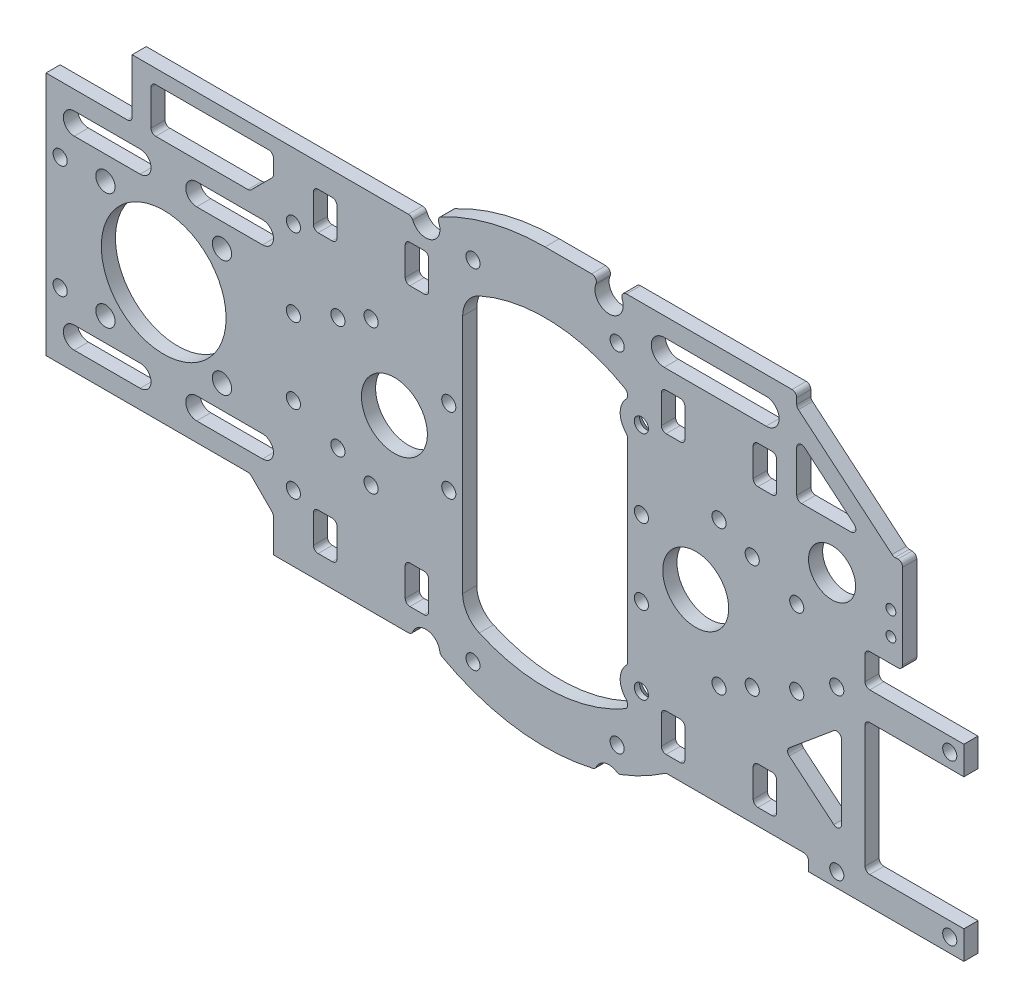
SolidWorks part; units mm, degrees
material "Thornel Mat VMA"
ref_plane "前视基准面" through (0, 0, 0) normal (0, 0, 1) x (1, 0, 0)
ref_plane "上视基准面" through (0, 0, 0) normal (0, 1, 0) x (1, 0, 0)
ref_plane "右视基准面" through (0, 0, 0) normal (1, 0, 0) x (0, 0, -1)
sketch "草图1" plane through (0, 0, 0) normal (0, 0, 1) x (1, 0, 0)
  line L0 (75, 47) -> (-112, 47) construction
  line L1 (-112, 47) -> (-112, -47) construction
  line L2 (-112, -47) -> (75, -47) construction
  line L3 (0, 0) -> (-81, 0) construction
  line L4 (75, -47) -> (75, 47) construction
  line L5 (-20.455, 8) -> (-20.455, -8) construction
  line L6 (-53.455, 8) -> (-53.455, -8) construction
  line L7 (0, 0) -> (0, 15.4871) construction
  line L8 (-36.955, 15.3) -> (-36.955, -15.3) construction
  line L9 (-17.5, 29.1505) -> (-17.5, -29.1505)
  line L10 (17.5, 29.1505) -> (17.5, 27.8938)
  line L11 (0, 0) -> (-15.3073, 36.9552) construction
  line L12 (-53.455, 8) -> (-53.455, 24.5) construction
  line L13 (44, -12) -> (-44, -12) construction
  line L14 (44, -12) -> (44, 12) construction
  line L15 (44, 12) -> (-44, 12) construction
  line L16 (-44, -12) -> (-44, 12) construction
  line L17 (44, -12) -> (-44, 12) construction
  line L18 (44, 12) -> (-44, -12) construction
  line L19 (20.455, -8) -> (20.455, 8) construction
  line L20 (17.5, -27.8938) -> (17.5, -29.1505)
  line L21 (17.5, 21.1062) -> (17.5, -21.1062)
  line L22 (-29.705, -33.5) -> (-24.705, -33.5)
  line L23 (-27.205, 29.5) -> (-46.705, 29.5) construction
  line L24 (-27.205, 29.5) -> (-27.205, -29.5) construction
  line L25 (-27.205, -29.5) -> (-46.705, -29.5) construction
  line L26 (-46.705, 29.5) -> (-46.705, -29.5) construction
  line L27 (-27.205, 29.5) -> (-46.705, -29.5) construction
  line L28 (-27.205, -29.5) -> (-46.705, 29.5) construction
  line L29 (-44.205, -25.5) -> (-49.205, -25.5)
  line L30 (-44.205, -25.5) -> (-44.205, -33.5)
  line L31 (-44.205, -33.5) -> (-49.205, -33.5)
  line L32 (-49.205, -25.5) -> (-49.205, -33.5)
  line L33 (-44.205, -25.5) -> (-49.205, -33.5) construction
  line L34 (-44.205, -33.5) -> (-49.205, -25.5) construction
  line L35 (-24.705, -25.5) -> (-24.705, -33.5)
  line L36 (-29.705, -25.5) -> (-24.705, -25.5)
  line L37 (-29.705, -25.5) -> (-29.705, -33.5)
  line L38 (-29.705, 25.5) -> (-29.705, 33.5)
  line L39 (-29.705, 25.5) -> (-24.705, 25.5)
  line L40 (-24.705, 25.5) -> (-24.705, 33.5)
  line L41 (-29.705, 33.5) -> (-24.705, 33.5)
  line L42 (-44.205, 33.5) -> (-49.205, 33.5)
  line L43 (-49.205, 25.5) -> (-49.205, 33.5)
  line L44 (-44.205, 25.5) -> (-49.205, 25.5)
  line L45 (-44.205, 25.5) -> (-44.205, 33.5)
  line L46 (29.705, 25.5) -> (24.705, 25.5)
  line L47 (24.705, 25.5) -> (24.705, 33.5)
  line L48 (29.705, 33.5) -> (24.705, 33.5)
  line L49 (29.705, 25.5) -> (29.705, 33.5)
  line L50 (44.205, 25.5) -> (44.205, 33.5)
  line L51 (44.205, 25.5) -> (49.205, 25.5)
  line L52 (49.205, 25.5) -> (49.205, 33.5)
  line L53 (44.205, 33.5) -> (49.205, 33.5)
  line L54 (29.705, -25.5) -> (29.705, -33.5)
  line L55 (29.705, -25.5) -> (24.705, -25.5)
  line L56 (24.705, -25.5) -> (24.705, -33.5)
  line L57 (29.705, -33.5) -> (24.705, -33.5)
  line L58 (44.205, -33.5) -> (49.205, -33.5)
  line L59 (49.205, -25.5) -> (49.205, -33.5)
  line L60 (44.205, -25.5) -> (49.205, -25.5)
  line L61 (44.205, -25.5) -> (44.205, -33.5)
  line L62 (0, 47) -> (75, 47) construction
  line L67 (-106, -26) -> (-57.705, -26)
  line L69 (68.955, 27.0448) -> (58.955, 27.0448) construction
  line L70 (68.955, 27.0448) -> (68.955, 41.9552) construction
  line L71 (68.955, 41.9552) -> (58.955, 41.9552) construction
  line L72 (58.955, 27.0448) -> (58.955, 41.9552) construction
  line L73 (68.955, 27.0448) -> (58.955, 41.9552) construction
  line L74 (68.955, 41.9552) -> (58.955, 27.0448) construction
  line L75 (75, 47) -> (75, 22.0448) construction
  line L76 (75, 22.0448) -> (75.955, 22.0448) construction
  line L77 (55.955, 22.0448) -> (55.955, 9.0448) construction
  line L78 (55.955, -36.9552) -> (25.6771, -36.9552)
  line L79 (-26.9583, 38.5) -> (-57.705, 38.5)
  line L80 (-23.297, -38.5) -> (-57.705, -38.5)
  line L84 (-57.705, -26) -> (-106, -26) construction
  line L85 (-106, -26) -> (-106, 26)
  line L86 (-106, 26) -> (-57.705, 26) construction
  line L87 (-57.705, 26) -> (-57.705, 38.5) construction
  line L88 (-100, 19.6872) -> (-86, 19.6872) construction
  line L91 (-100, 22) -> (-86, 22)
  line L92 (-100, 17.3744) -> (-86, 17.3744)
  line L93 (-74, 19.6872) -> (-60, 19.6872) construction
  line L94 (-74, 22) -> (-60, 22)
  line L95 (-74, 17.3744) -> (-60, 17.3744)
  line L96 (-100, -19.6872) -> (-86, -19.6872) construction
  line L97 (-100, -22) -> (-86, -22)
  line L98 (-100, -17.3744) -> (-86, -17.3744)
  line L99 (-74, -19.6872) -> (-60, -19.6872) construction
  line L100 (-74, -22) -> (-60, -22)
  line L101 (-74, -17.3744) -> (-60, -17.3744)
  line L102 (25.3073, 40.25) -> (46.955, 40.25) construction
  line L103 (25.3073, 43) -> (46.955, 43)
  line L104 (25.3073, 37.5) -> (46.955, 37.5)
  line L105 (67.955, 22.0448) -> (67.955, 9.0448) construction
  line L106 (67.955, 9.0448) -> (63.955, 9.0448) construction
  line L109 (63.955, 22.0448) -> (63.955, 9.0448) construction
  line L110 (60.955, 22.0448) -> (60.955, 9.0448) construction
  line L111 (60.955, 22.0448) -> (55.955, 22.0448) construction
  line L112 (55.955, -22.9552) -> (55.955, -36.9552) construction
  line L113 (67.955, 22.0448) -> (63.955, 22.0448) construction
  line L114 (60.955, 9.0448) -> (55.955, 9.0448) construction
  line L115 (55.955, -22.9552) -> (67.955, -22.9552) construction
  line L116 (75.955, 7.0448) -> (75.955, 22.0448) construction
  line L117 (61.955, -22.9552) -> (61.955, -2.9552) construction
  line L119 (-57.705, -26) -> (-57.705, -38.5)
  line L121 (53.455, 47) -> (53.455, 44.2664)
  line L122 (53.455, 27.0448) -> (67.756, 27.0448)
  line L123 (75.955, 27.0448) -> (75.955, 22.0448) construction
  line L124 (0, 47) -> (53.455, 47)
  line L130 (-87.705, 26) -> (-87.705, 38.5)
  line L131 (-87.705, 38.5) -> (-57.705, 38.5)
  line L132 (-87.705, 26) -> (-106, 26)
  line L133 (67.955, -22.9552) -> (67.955, -6)
  line L134 (-83.705, 35.5) -> (-57.705, 35.5)
  line L135 (-83.705, 35.5) -> (-83.705, 26)
  line L136 (-83.705, 26) -> (-57.705, 26)
  line L137 (-57.705, 35.5) -> (-57.705, 26)
  line L138 (-83.705, 35.5) -> (-57.705, 26) construction
  line L139 (-83.705, 26) -> (-57.705, 35.5) construction
  line L140 (67.955, 7.0448) -> (75.955, 7.0448)
  line L142 (67.955, -33.9552) -> (67.955, -22.9552)
  line L143 (55.955, -36.9552) -> (55.955, -39.9552)
  line L146 (55.955, -39.9552) -> (88.955, -39.9552)
  line L147 (88.955, -39.9552) -> (88.955, -33.9552)
  line L148 (88.955, -33.9552) -> (67.955, -33.9552)
  line L149 (67.955, -6) -> (88.955, -6)
  line L150 (88.955, -6) -> (88.955, 0)
  line L151 (88.955, 0) -> (67.955, 0) construction
  line L152 (67.955, 0) -> (67.955, 7.0448)
  line L153 (62.955, -29.9552) -> (62.955, -9.9552)
  line L154 (62.955, -9.9552) -> (50.955, -19.9552)
  line L155 (50.955, -19.9552) -> (62.955, -29.9552)
  line L156 (62.955, -19.9552) -> (50.955, -19.9552) construction
  line L157 (75.955, 27.0448) -> (102.955, 27.0448) construction
  line L158 (102.955, 27.0448) -> (102.955, 12.0448) construction
  line L159 (102.955, 12.0448) -> (75.955, 12.0448) construction
  line L160 (75.955, 12.0448) -> (75.955, 7.0448)
  line L161 (91.455, 16.5448) -> (99.455, 16.5448) construction
  line L162 (95.455, 16.5448) -> (95.455, 19.1666) construction
  line L163 (53.455, 39.0448) -> (67.756, 27.0448)
  line L164 (53.455, 44.2664) -> (73.9789, 27.0448)
  line L165 (53.455, 39.0448) -> (53.455, 27.0448)
  line L166 (73.9789, 27.0448) -> (75.955, 27.0448)
  line L167 (102.955, 12.0448) -> (88.955, 0) construction
  line L168 (96.8218, 12.0448) -> (82.8218, 0) construction
  line L169 (75.955, 12.0448) -> (96.8218, 12.0448) construction
  line L170 (67.955, 0) -> (82.8218, 0)
  line L171 (75.955, 12.0448) -> (75.955, 27.0448)
  line L172 (88.955, 0) -> (82.8218, 0)
  arc A0 (-17.5, -29.1505) -> (17.5, -29.1505) centre (0, 0) ccw
  circle A2 centre (-81, 0) radius 13.25
  circle A3 centre (-81, 0) radius 17.5 construction
  circle A4 centre (-93.3744, 12.3744) radius 2.05
  circle A5 centre (-68.6256, 12.3744) radius 2.05
  circle A6 centre (-68.6256, -12.3744) radius 2.05
  circle A7 centre (-93.3744, -12.3744) radius 2.05
  circle A8 centre (-20.455, 8) radius 1.5
  circle A9 centre (-20.455, -8) radius 1.5
  circle A10 centre (-53.455, 8) radius 1.5
  circle A11 centre (-53.455, -8) radius 1.5
  circle A12 centre (20.455, -8) radius 1.5
  circle A13 centre (20.455, 8) radius 1.5
  circle A14 centre (53.455, -8) radius 1.5
  circle A15 centre (53.455, 8) radius 1.5
  circle A16 centre (-36.955, 15.3) radius 1.5
  circle A17 centre (-36.955, -15.3) radius 1.5
  circle A18 centre (36.955, -15.3) radius 1.5
  circle A19 centre (36.955, 15.3) radius 1.5
  circle A20 centre (0, 0) radius 40 construction
  arc A21 (17.5, 29.1505) -> (-17.5, 29.1505) centre (0, 0) ccw
  circle A22 centre (-15.3073, 36.9552) radius 1.5
  circle A23 centre (-15.3073, -36.9552) radius 1.5
  circle A24 centre (15.3073, -36.9552) radius 1.5
  circle A25 centre (15.3073, 36.9552) radius 1.5
  circle A26 centre (44, 12) radius 1.5
  circle A27 centre (44, -12) radius 1.5
  circle A28 centre (-44, 12) radius 1.5
  circle A29 centre (-44, -12) radius 1.5
  circle A30 centre (-53.455, 24.5) radius 1.5
  circle A31 centre (-53.455, -24.5) radius 1.5
  circle A32 centre (20.455, -24.5) radius 1.5
  circle A33 centre (20.455, 24.5) radius 1.5
  arc A34 (17.5, -21.1062) -> (17.5, -27.8938) centre (20.455, -24.5) ccw
  arc A35 (17.5, 27.8938) -> (17.5, 21.1062) centre (20.455, 24.5) ccw
  circle A40 centre (-103, 12) radius 1.5
  circle A41 centre (-103, -12) radius 1.5
  arc A43 (-26.9583, 38.5) -> (0, 47) centre (0, 0) cw
  arc A44 (-23.297, -38.5) -> (25.6771, -36.9552) centre (0, 0) ccw
  arc A47 (-100, 22) -> (-100, 17.3744) centre (-100, 19.6872) ccw
  arc A48 (-86, 17.3744) -> (-86, 22) centre (-86, 19.6872) ccw
  arc A49 (-74, 22) -> (-74, 17.3744) centre (-74, 19.6872) ccw
  arc A50 (-60, 17.3744) -> (-60, 22) centre (-60, 19.6872) ccw
  arc A51 (-100, -22) -> (-100, -17.3744) centre (-100, -19.6872) cw
  arc A52 (-86, -17.3744) -> (-86, -22) centre (-86, -19.6872) cw
  arc A53 (-74, -22) -> (-74, -17.3744) centre (-74, -19.6872) cw
  arc A54 (-60, -17.3744) -> (-60, -22) centre (-60, -19.6872) cw
  arc A55 (25.3073, 43) -> (25.3073, 37.5) centre (25.3073, 40.25) ccw
  arc A56 (46.955, 37.5) -> (46.955, 43) centre (46.955, 40.25) ccw
  circle A57 centre (61.955, -36.9552) radius 1.5
  circle A58 centre (61.955, -2.9552) radius 1.5
  circle A59 centre (73.455, 12) radius 1.05
  circle A60 centre (73.455, 17) radius 1.05
  circle A61 centre (85.955, -36.9552) radius 1.5
  circle A62 centre (85.955, -2.9552) radius 1.5
  circle A63 centre (32, 0) radius 7
  circle A64 centre (-32, 0) radius 7
  circle A65 centre (60.955, 17.5448) radius 5
  circle A66 centre (91.455, 16.5448) radius 1.55 construction
  circle A67 centre (99.455, 16.5448) radius 1.55 construction
  circle A68 centre (95.455, 23.5448) radius 1.55 construction
  point P21 (-81, 0)
  point P69 (-36.955, 0)
  point P113 (-63.955, -34.5)
  point P114 (-70.705, 30.75)
  point P118 (63.955, 34.5)
  point P144 (-93, 19.6872)
  point P149 (-67, 19.6872)
  point P156 (36.1312, 40.25)
  point P159 (-93, -19.6872)
  point P166 (-67, -19.6872)
  dimension "D1" = 68
  dimension "D2" = 94
  dimension "D5" = 26.5
  dimension "D8" = 35
  dimension "D9" = 4.1
  dimension "D10" = 3
  dimension "D17" = 80
  dimension "D22" = 9
  dimension "D35" = 5
  dimension "D36" = 5
  dimension "D52" = 10
  dimension "D62" = 2.1
  dimension "D76" = 14
  dimension "D78" = 10
  dimension "D83" = 3.1
  dimension "D3" = 112
  dimension "D4" = 75
  dimension "D6" = 81
  dimension "D11" = 16
  dimension "D12" = 40.91
  dimension "D13" = 33
  dimension "D14" = 73.91
  dimension "D15" = 30.6
  dimension "D16" = 35
  dimension "D18" = 22.5
  dimension "D19" = 24
  dimension "D20" = 88
  dimension "D21" = 49
  dimension "D23" = 8
  dimension "D24" = 5
  dimension "D25" = 19.5
  dimension "D26" = 59
  dimension "D27" = 10.5
  dimension "D28" = 30
  dimension "D29" = 3
  dimension "D30" = 34.5
  dimension "D31" = 34.5
  dimension "D32" = 10.5
  dimension "D33" = 12
  dimension "D34" = 22
  dimension "D37" = 2.5
  dimension "D38" = 5
  dimension "D39" = 5
  dimension "D40" = 4
  dimension "D41" = 4
  dimension "D42" = 8.5
  dimension "D43" = 52
  dimension "D44" = 3
  dimension "D45" = 4
  dimension "D46" = 5
  dimension "D47" = 6
  dimension "D48" = 14
  dimension "D49" = 12
  dimension "D50" = 4
  dimension "D51" = 4
  dimension "D53" = 12
  dimension "D54" = 8
  dimension "D55" = 32
  dimension "D56" = 12
  dimension "D57" = 13
  dimension "D58" = 3
  dimension "D59" = 34
  dimension "D60" = 3
  dimension "D61" = 14
  dimension "D63" = 5
  dimension "D64" = 2.5
  dimension "D65" = 6
  dimension "D66" = 12
  dimension "D67" = 12
  dimension "D68" = 30
  dimension "D69" = 3
  dimension "D70" = 24
  dimension "D71" = 3
  dimension "D72" = 3
  dimension "D73" = 20
  dimension "D74" = 5
  dimension "D75" = 12
  dimension "D77" = 32
  dimension "D79" = 9.5
  dimension "D80" = 6.5
  dimension "D81" = 15
  dimension "D82" = 19.5
  dimension "D84" = 7
  dimension "D85" = 8
  dimension "D86" = 3.5
  dimension "D87" = 3.5
  dimension "D88" = 4
  dimension "D89" = 12
  dimension "D90" = 40
  dimension "D91" = 4
  dimension "D7" = 4
extrude "凸台-拉伸1" add sketch "草图1" along normal blind 3
hole_wizard "M3 六角凹锥坑螺钉的锥形沉头孔1" positions "3D草图1" profile "草图2" countersink size "M3" standard "ISO" end condition through all
sketch3d "3D草图1"
  line L5 (20.455, -24.5, 3) -> (20.455, -24.5, 0) construction
  line L6 (20.455, -24.5, 3) -> (20.455, -24.5, 0) construction
  line L7 (20.455, 24.5, 3) -> (20.455, 24.5, 0) construction
  point P22 (20.455, -24.5, 0)
  point P28 (20.455, 24.5, 0)
sketch "草图2" plane through (20.455, -24.5, 0) normal (1, 0, 0) x (0, 1, 0)
  line L0 (0, 0) -> (0, 3)
  line L1 (0, 3) -> (1.5, 3)
  line L2 (1.5, 3) -> (1.5, 1.86)
  line L3 (1.5, 1.86) -> (3.36, 0)
  line L5 (3.36, 0) -> (0, 0)
  line L6 (-1.5, 1.86) -> (-3.36, 0) construction
  line L11 (0, -6.35) -> (0, 107.95) construction
  dimension "通孔孔直径" = 3
  dimension "通孔孔深度" = 3
  dimension "近端锥形沉头孔直径" = 6.72
  dimension "近端锥形沉头孔角度" = 90
fillet "圆角2" radius 6 3 edges at (-17.5, 29.1505, 1.5) (-17.5, -29.1505, 1.5) (-26.9583, 38.5, 1.5)
chamfer "倒角1" distance 5 angle 45 2 edges at (-57.705, 26, 1.5) (-57.705, -26, 1.5)
fillet "圆角1" radius 1 64 edges at (49.205, -33.5, 1.5) (49.205, -25.5, 1.5) (44.205, -25.5, 1.5) (44.205, -33.5, 1.5) (24.705, -33.5, 1.5) (29.705, -33.5, 1.5) (29.705, -25.5, 1.5) (24.705, -25.5, 1.5) (49.205, 33.5, 1.5) (44.205, 33.5, 1.5) (44.205, 25.5, 1.5) (49.205, 25.5, 1.5) (24.705, 33.5, 1.5) (24.705, 25.5, 1.5) (29.705, 25.5, 1.5) (29.705, 33.5, 1.5) (-49.205, 33.5, 1.5) (-49.205, 25.5, 1.5) (-44.205, 25.5, 1.5) (-44.205, 33.5, 1.5) (-24.705, 33.5, 1.5) (-29.705, 33.5, 1.5) (-29.705, 25.5, 1.5) (-24.705, 25.5, 1.5) (-24.705, -33.5, 1.5) (-24.705, -25.5, 1.5) (-29.705, -25.5, 1.5) (-29.705, -33.5, 1.5) (-44.205, -33.5, 1.5) (-44.205, -25.5, 1.5) (-49.205, -25.5, 1.5) (17.5, -29.1505, 1.5) (17.5, -27.8938, 1.5) (17.5, -21.1062, 1.5) (17.5, 21.1062, 1.5) (17.5, 27.8938, 1.5) (17.5, 29.1505, 1.5) (-49.205, -33.5, 1.5) (50.955, -19.9552, 1.5) (62.955, -9.9552, 1.5) (62.955, -29.9552, 1.5) (53.455, 39.0448, 1.5) (67.756, 27.0448, 1.5) (53.455, 27.0448, 1.5) (-83.705, 26, 1.5) (-57.705, 35.5, 1.5) (-87.705, 26, 1.5) (53.455, 44.2664, 1.5) (67.955, 7.0448, 1.5) (67.955, -6, 1.5) (67.955, -33.9552, 1.5) (55.955, -36.9552, 1.5) (25.6771, -36.9552, 1.5) (-23.297, -38.5, 1.5) (-83.705, 35.5, 1.5) (-62.705, 26, 1.5) (-57.705, -31, 1.5) (-62.705, -26, 1.5) (-57.705, 31, 1.5) (53.455, 47, 1.5) (67.955, 0, 1.5) (73.9789, 27.0448, 1.5) (75.955, 7.0448, 1.5) (75.955, 27.0448, 1.5)
sketch "草图3" plane through (0, 0, 0) normal (0, 0, -1) x (-1, 0, 0)
  line L0 (0, 0) -> (10.8077, 0) construction
  line L1 (0, 0) -> (-13.5953, 44.4682) construction
  line L2 (25.3257, 38.9982) -> (0, 0) construction
  circle A0 centre (0, 0) radius 46.5 construction
  circle A1 centre (25.3257, 38.9982) radius 3
  circle A2 centre (-13.5953, 44.4682) radius 3
  circle A3 centre (-13.5953, -44.4682) radius 3
  circle A4 centre (25.3257, -38.9982) radius 3
  point P7 (10.8077, 0)
  point P9 (-18.5014, 42.6608)
  point P10 (-14.1626, 44.2907)
  dimension "D1" = 93
  dimension "D3" = 6
  dimension "D2" = 50
  dimension "D4" = 57
extrude "切除-拉伸1" cut sketch "草图3" against normal blind 10
fillet "圆角3" radius 1 8 edges at (15.2046, 47, 1.5) (11.986, 47, 1.5) (-23.0539, 40.9575, 1.5) (-28.2875, 38.5209, 1.5) (15.5787, -42.2174, 1.5) (10.6923, -43.7113, 1.5) (-22.3266, -39.0707, 1.5) (-28.2841, -38.5, 1.5)
